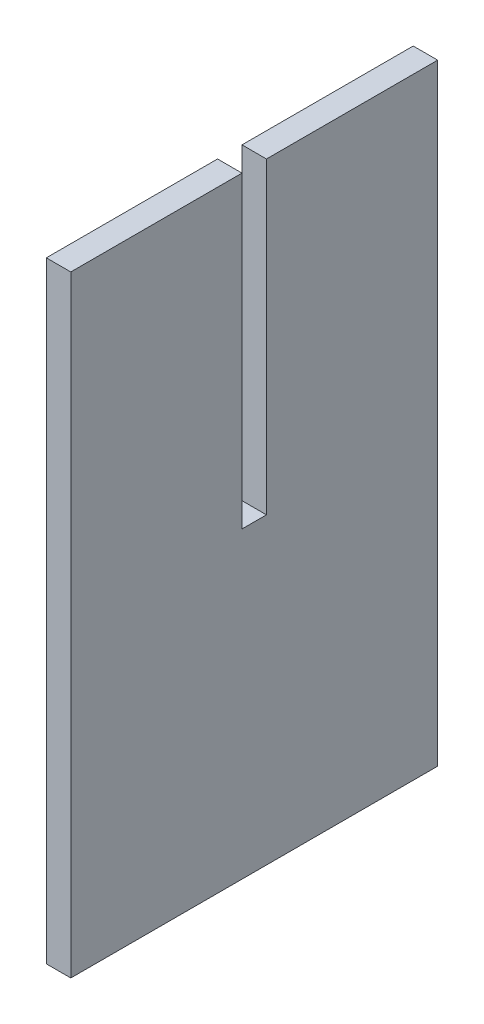
SolidWorks part; units mm, degrees
ref_plane "前视基准面" through (0, 0, 0) normal (0, 0, 1) x (1, 0, 0)
ref_plane "上视基准面" through (0, 0, 0) normal (0, 1, 0) x (1, 0, 0)
ref_plane "右视基准面" through (0, 0, 0) normal (1, 0, 0) x (0, 0, -1)
other "Configuration Table"
sketch "草图1" plane through (0, 0, 0) normal (1, 0, 0) x (0, 0, -1)
  line L1 (0, 0) -> (30, 0)
  line L2 (0, 0) -> (0, -50)
  line L3 (0, -50) -> (30, -50)
  line L4 (30, 0) -> (30, -50)
  dimension "D1" = 30
  dimension "D2" = 50
extrude "凸台-拉伸1" add sketch "草图1" along normal blind 2
sketch "草图2" plane through (2, 0, 0) normal (1, 0, 0) x (0, 0, -1)
  line L0 (30, 0) -> (0, 0) construction
  line L1 (14, 0) -> (16, 0)
  line L2 (14, 0) -> (14, -25.2)
  line L3 (14, -25.2) -> (16, -25.2)
  line L4 (16, 0) -> (16, -25.2)
  point P6 (15, 0)
  point P7 (15, 0)
  dimension "D1" = 0
  dimension "D2" = 2
  dimension "D3" = 25.2
extrude "切除-拉伸1" cut sketch "草图2" against normal blind 2
